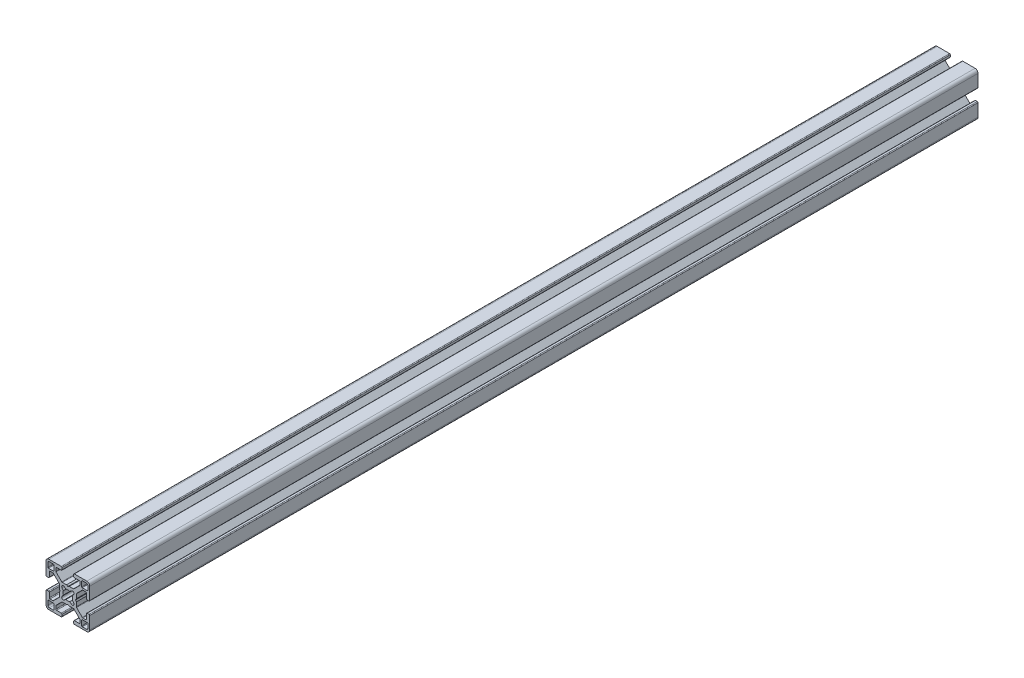
SolidWorks part; units mm, degrees
ref_plane "Front" through (0, 0, 0) normal (0, 0, 1) x (1, 0, 0)
ref_plane "Top" through (0, 0, 0) normal (0, 1, 0) x (1, 0, 0)
ref_plane "Right" through (0, 0, 0) normal (1, 0, 0) x (0, 0, -1)
ref_plane "Plane1" through (0, 0, -25) normal (0, 0, -1) x (-1, 0, 0)
sketch "Sketch1" plane through (0, 0, -25) normal (0, 0, -1) x (-1, 0, 0)
  line L0 (13.7, -9.881) -> (13.7, -12.7)
  line L1 (12.7, -13.7) -> (9.881, -13.7)
  line L2 (9.5, -13.319) -> (9.5, -9.881)
  line L3 (9.881, -9.5) -> (13.319, -9.5)
  line L4 (13.7, 12.7) -> (13.7, 9.881)
  line L5 (13.319, 9.5) -> (9.881, 9.5)
  line L6 (9.5, 9.881) -> (9.5, 13.319)
  line L7 (9.881, 13.7) -> (12.7, 13.7)
  line L8 (3.0544, -1.3138) -> (4.0107, -2.5139)
  line L9 (2.5139, -4.0107) -> (1.3138, -3.0544)
  line L10 (-1.3138, -3.0544) -> (-2.5139, -4.0107)
  line L11 (-4.0107, -2.5139) -> (-3.0544, -1.3138)
  line L12 (-3.0544, 1.3138) -> (-4.0107, 2.5139)
  line L13 (-2.5139, 4.0107) -> (-1.3138, 3.0544)
  line L14 (1.3138, 3.0544) -> (2.5139, 4.0107)
  line L15 (4.0107, 2.5139) -> (3.0544, 1.3138)
  line L16 (-9.5, 13.319) -> (-9.5, 9.881)
  line L17 (-9.881, 9.5) -> (-13.319, 9.5)
  line L18 (-13.7, 9.881) -> (-13.7, 12.7)
  line L19 (-12.7, 13.7) -> (-9.881, 13.7)
  line L20 (-9.5, -9.881) -> (-9.5, -13.319)
  line L21 (-9.881, -13.7) -> (-12.7, -13.7)
  line L22 (-13.7, -12.7) -> (-13.7, -9.881)
  line L23 (-13.319, -9.5) -> (-9.881, -9.5)
  line L24 (15, -13) -> (15, -4.508)
  line L25 (14.492, -4) -> (13.251, -4)
  line L26 (12.743, -4.508) -> (12.743, -7.742)
  line L27 (12.235, -8.25) -> (10.2629, -8.25)
  line L28 (9.9037, -8.1012) -> (5.9833, -4.1808)
  line L29 (5.8345, -3.8216) -> (5.8345, -0.949)
  line L30 (5.8345, -0.949) -> (5.325, 0)
  line L31 (5.325, 0) -> (5.8345, 0.949)
  line L32 (5.8345, 0.949) -> (5.8345, 3.8203)
  line L33 (5.9833, 4.1795) -> (9.905, 8.1012)
  line L34 (10.2642, 8.25) -> (12.235, 8.25)
  line L35 (12.743, 7.742) -> (12.743, 4.508)
  line L36 (13.251, 4) -> (14.492, 4)
  line L37 (15, 4.508) -> (15, 13)
  line L38 (13, 15) -> (4.508, 15)
  line L39 (4, 14.492) -> (4, 13.251)
  line L40 (4.508, 12.743) -> (7.742, 12.743)
  line L41 (8.25, 12.235) -> (8.25, 10.2629)
  line L42 (8.1012, 9.9037) -> (4.1808, 5.9833)
  line L43 (3.8216, 5.8345) -> (0.949, 5.8345)
  line L44 (0.949, 5.8345) -> (0, 5.325)
  line L45 (0, 5.325) -> (-0.949, 5.8345)
  line L46 (-0.949, 5.8345) -> (-3.8203, 5.8345)
  line L47 (-4.1795, 5.9833) -> (-8.1012, 9.905)
  line L48 (-8.25, 10.2642) -> (-8.25, 12.235)
  line L49 (-7.742, 12.743) -> (-4.508, 12.743)
  line L50 (-4, 13.251) -> (-4, 14.492)
  line L51 (-4.508, 15) -> (-13, 15)
  line L52 (-15, 13) -> (-15, 4.508)
  line L53 (-14.492, 4) -> (-13.251, 4)
  line L54 (-12.743, 4.508) -> (-12.743, 7.742)
  line L55 (-12.235, 8.25) -> (-10.2629, 8.25)
  line L56 (-9.9037, 8.1012) -> (-5.9833, 4.1808)
  line L57 (-5.8345, 3.8216) -> (-5.8345, 0.949)
  line L58 (-5.8345, 0.949) -> (-5.325, 0)
  line L59 (-5.325, 0) -> (-5.8345, -0.949)
  line L60 (-5.8345, -0.949) -> (-5.8345, -3.8203)
  line L61 (-5.9833, -4.1795) -> (-9.905, -8.1012)
  line L62 (-10.2642, -8.25) -> (-12.235, -8.25)
  line L63 (-12.743, -7.742) -> (-12.743, -4.508)
  line L64 (-13.251, -4) -> (-14.492, -4)
  line L65 (-15, -4.508) -> (-15, -13)
  line L66 (-13, -15) -> (-4.508, -15)
  line L67 (-4, -14.492) -> (-4, -13.251)
  line L68 (-4.508, -12.743) -> (-7.742, -12.743)
  line L69 (-8.25, -12.235) -> (-8.25, -10.2629)
  line L70 (-8.1012, -9.9037) -> (-4.1808, -5.9833)
  line L71 (-3.8216, -5.8345) -> (-0.949, -5.8345)
  line L72 (-0.949, -5.8345) -> (0, -5.325)
  line L73 (0, -5.325) -> (0.949, -5.8345)
  line L74 (0.949, -5.8345) -> (3.8203, -5.8345)
  line L75 (4.1795, -5.9833) -> (8.1012, -9.905)
  line L76 (8.25, -10.2642) -> (8.25, -12.235)
  line L77 (7.742, -12.743) -> (4.508, -12.743)
  line L78 (4, -13.251) -> (4, -14.492)
  line L79 (4.508, -15) -> (13, -15)
  arc A0 (13.7, -12.7) -> (12.7, -13.7) centre (12.7, -12.7) cw
  arc A1 (9.881, -13.7) -> (9.5, -13.319) centre (9.881, -13.319) cw
  arc A2 (9.5, -9.881) -> (9.881, -9.5) centre (9.881, -9.881) cw
  arc A3 (13.319, -9.5) -> (13.7, -9.881) centre (13.319, -9.881) cw
  arc A4 (13.7, 9.881) -> (13.319, 9.5) centre (13.319, 9.881) cw
  arc A5 (9.881, 9.5) -> (9.5, 9.881) centre (9.881, 9.881) cw
  arc A6 (9.5, 13.319) -> (9.881, 13.7) centre (9.881, 13.319) cw
  arc A7 (12.7, 13.7) -> (13.7, 12.7) centre (12.7, 12.7) cw
  arc A8 (4.0107, -2.5139) -> (2.5139, -4.0107) centre (3.142, -3.142) cw
  arc A9 (1.3138, -3.0544) -> (-1.3138, -3.0544) centre (0, 0) cw
  arc A10 (-2.5139, -4.0107) -> (-4.0107, -2.5139) centre (-3.142, -3.142) cw
  arc A11 (-3.0544, -1.3138) -> (-3.0544, 1.3138) centre (0, 0) cw
  arc A12 (-4.0107, 2.5139) -> (-2.5139, 4.0107) centre (-3.142, 3.142) cw
  arc A13 (-1.3138, 3.0544) -> (1.3138, 3.0544) centre (0, 0) cw
  arc A14 (2.5139, 4.0107) -> (4.0107, 2.5139) centre (3.142, 3.142) cw
  arc A15 (3.0544, 1.3138) -> (3.0544, -1.3138) centre (0, 0) cw
  arc A16 (-9.5, 9.881) -> (-9.881, 9.5) centre (-9.881, 9.881) cw
  arc A17 (-13.319, 9.5) -> (-13.7, 9.881) centre (-13.319, 9.881) cw
  arc A18 (-13.7, 12.7) -> (-12.7, 13.7) centre (-12.7, 12.7) cw
  arc A19 (-9.881, 13.7) -> (-9.5, 13.319) centre (-9.881, 13.319) cw
  arc A20 (-9.5, -13.319) -> (-9.881, -13.7) centre (-9.881, -13.319) cw
  arc A21 (-12.7, -13.7) -> (-13.7, -12.7) centre (-12.7, -12.7) cw
  arc A22 (-13.7, -9.881) -> (-13.319, -9.5) centre (-13.319, -9.881) cw
  arc A23 (-9.881, -9.5) -> (-9.5, -9.881) centre (-9.881, -9.881) cw
  arc A24 (15, -4.508) -> (14.492, -4) centre (14.492, -4.508) ccw
  arc A25 (13.251, -4) -> (12.743, -4.508) centre (13.251, -4.508) ccw
  arc A26 (12.743, -7.742) -> (12.235, -8.25) centre (12.235, -7.742) cw
  arc A27 (10.2629, -8.25) -> (9.9037, -8.1012) centre (10.2629, -7.742) cw
  arc A28 (5.9833, -4.1808) -> (5.8345, -3.8216) centre (6.3425, -3.8216) cw
  arc A29 (5.8345, 3.8203) -> (5.9833, 4.1795) centre (6.3425, 3.8203) cw
  arc A30 (9.905, 8.1012) -> (10.2642, 8.25) centre (10.2642, 7.742) cw
  arc A31 (12.235, 8.25) -> (12.743, 7.742) centre (12.235, 7.742) cw
  arc A32 (12.743, 4.508) -> (13.251, 4) centre (13.251, 4.508) ccw
  arc A33 (14.492, 4) -> (15, 4.508) centre (14.492, 4.508) ccw
  arc A34 (15, 13) -> (13, 15) centre (13, 13) ccw
  arc A35 (4.508, 15) -> (4, 14.492) centre (4.508, 14.492) ccw
  arc A36 (4, 13.251) -> (4.508, 12.743) centre (4.508, 13.251) ccw
  arc A37 (7.742, 12.743) -> (8.25, 12.235) centre (7.742, 12.235) cw
  arc A38 (8.25, 10.2629) -> (8.1012, 9.9037) centre (7.742, 10.2629) cw
  arc A39 (4.1808, 5.9833) -> (3.8216, 5.8345) centre (3.8216, 6.3425) cw
  arc A40 (-3.8203, 5.8345) -> (-4.1795, 5.9833) centre (-3.8203, 6.3425) cw
  arc A41 (-8.1012, 9.905) -> (-8.25, 10.2642) centre (-7.742, 10.2642) cw
  arc A42 (-8.25, 12.235) -> (-7.742, 12.743) centre (-7.742, 12.235) cw
  arc A43 (-4.508, 12.743) -> (-4, 13.251) centre (-4.508, 13.251) ccw
  arc A44 (-4, 14.492) -> (-4.508, 15) centre (-4.508, 14.492) ccw
  arc A45 (-13, 15) -> (-15, 13) centre (-13, 13) ccw
  arc A46 (-15, 4.508) -> (-14.492, 4) centre (-14.492, 4.508) ccw
  arc A47 (-13.251, 4) -> (-12.743, 4.508) centre (-13.251, 4.508) ccw
  arc A48 (-12.743, 7.742) -> (-12.235, 8.25) centre (-12.235, 7.742) cw
  arc A49 (-10.2629, 8.25) -> (-9.9037, 8.1012) centre (-10.2629, 7.742) cw
  arc A50 (-5.9833, 4.1808) -> (-5.8345, 3.8216) centre (-6.3425, 3.8216) cw
  arc A51 (-5.8345, -3.8203) -> (-5.9833, -4.1795) centre (-6.3425, -3.8203) cw
  arc A52 (-9.905, -8.1012) -> (-10.2642, -8.25) centre (-10.2642, -7.742) cw
  arc A53 (-12.235, -8.25) -> (-12.743, -7.742) centre (-12.235, -7.742) cw
  arc A54 (-12.743, -4.508) -> (-13.251, -4) centre (-13.251, -4.508) ccw
  arc A55 (-14.492, -4) -> (-15, -4.508) centre (-14.492, -4.508) ccw
  arc A56 (-15, -13) -> (-13, -15) centre (-13, -13) ccw
  arc A57 (-4.508, -15) -> (-4, -14.492) centre (-4.508, -14.492) ccw
  arc A58 (-4, -13.251) -> (-4.508, -12.743) centre (-4.508, -13.251) ccw
  arc A59 (-7.742, -12.743) -> (-8.25, -12.235) centre (-7.742, -12.235) cw
  arc A60 (-8.25, -10.2629) -> (-8.1012, -9.9037) centre (-7.742, -10.2629) cw
  arc A61 (-4.1808, -5.9833) -> (-3.8216, -5.8345) centre (-3.8216, -6.3425) cw
  arc A62 (3.8203, -5.8345) -> (4.1795, -5.9833) centre (3.8203, -6.3425) cw
  arc A63 (8.1012, -9.905) -> (8.25, -10.2642) centre (7.742, -10.2642) cw
  arc A64 (8.25, -12.235) -> (7.742, -12.743) centre (7.742, -12.235) cw
  arc A65 (4.508, -12.743) -> (4, -13.251) centre (4.508, -13.251) ccw
  arc A66 (4, -14.492) -> (4.508, -15) centre (4.508, -14.492) ccw
  arc A67 (13, -15) -> (15, -13) centre (13, -13) ccw
extrude "Boss-Extrude1" add sketch "Sketch1" against normal blind 609.6
